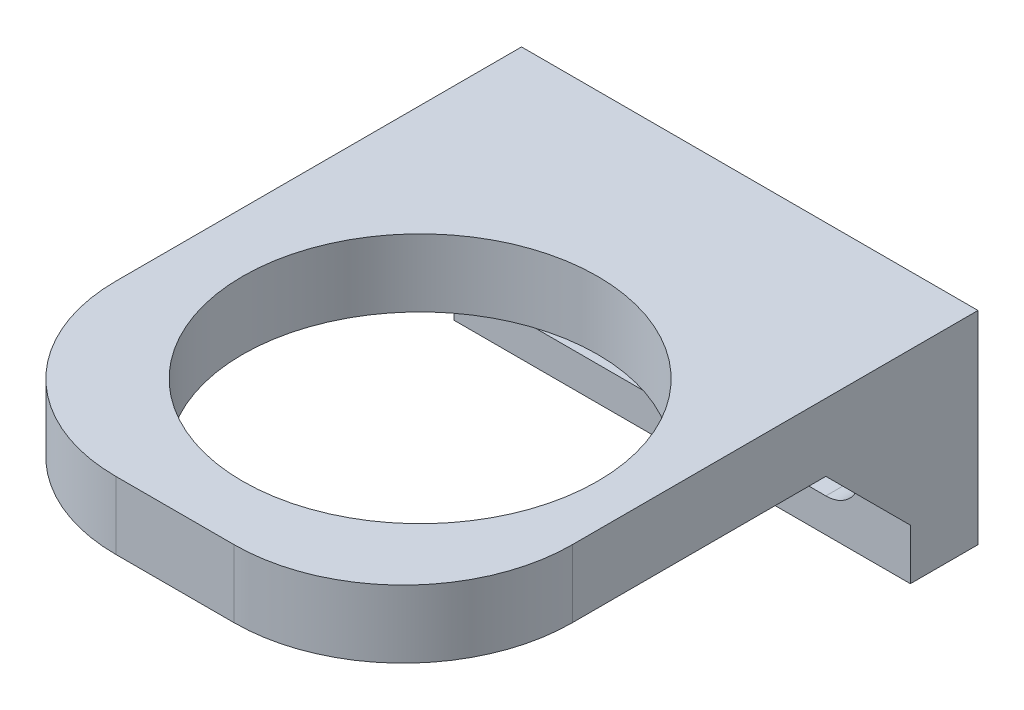
SolidWorks part; units mm, degrees
ref_plane "Plan de face" through (0, 0, 0) normal (0, 0, 1) x (1, 0, 0)
ref_plane "Plan de dessus" through (0, 0, 0) normal (0, 1, 0) x (1, 0, 0)
ref_plane "Plan de droite" through (0, 0, 0) normal (1, 0, 0) x (0, 0, -1)
sketch "Esquisse1" plane through (0, 0, 0) normal (0, 1, 0) x (1, 0, 0)
  line L1 (-14, 20) -> (13, 20)
  line L2 (-14, 20) -> (-14, -14)
  line L3 (-14, -14) -> (13, -14)
  line L4 (13, 20) -> (13, -14)
  line L6 (-14, 0) -> (13, 0) construction
  circle A0 centre (0, 0) radius 10.5
  dimension "D1" = 21
  dimension "D2" = 27
  dimension "D3" = 34
  dimension "D4" = 14
  dimension "D5" = 13
extrude "Boss.-Extru.1" add sketch "Esquisse1" along normal blind 4
sketch "Esquisse2" plane through (0, 0, 0) normal (0, -1, 0) x (1, 0, 0)
  line L0 (13, 14) -> (13, -20) construction
  line L1 (-14, -20) -> (13, -20)
  line L2 (-14, -20) -> (-14, -16)
  line L3 (-14, -16) -> (13, -16)
  line L4 (13, -20) -> (13, -16)
  dimension "D1" = 4
extrude "Boss.-Extru.2" add sketch "Esquisse2" along normal blind 8
sketch "Esquisse5" plane through (-14, 0, 0) normal (-1, 0, 0) x (0, 0, 1)
  line L0 (-16, 0) -> (-16, -5)
  line L1 (-16, -8) -> (-16, 0) construction
  line L2 (-16, -5) -> (-11, 0)
  line L3 (-16, 0) -> (14, 0) construction
  line L4 (-11, 0) -> (-16, 0)
  dimension "D1" = 45
  dimension "D2" = 5
extrude "Boss.-Extru.3" add sketch "Esquisse5" against normal blind 2
sketch "Esquisse6" plane through (13, 0, 0) normal (1, 0, 0) x (0, 0, -1)
  line L0 (16, 0) -> (11, 0)
  line L1 (-14, 0) -> (16, 0) construction
  line L2 (11, 0) -> (16, -5)
  line L3 (16, -8) -> (16, 0) construction
  line L4 (16, -5) -> (16, 0)
  dimension "D1" = 45
  dimension "D2" = 5
extrude "Boss.-Extru.4" add sketch "Esquisse6" against normal blind 2
fillet "Congé1" radius 10 2 edges at (-14, 2, 14) (13, 2, 14)
sketch "Esquisse7" plane through (0, 0, -16) normal (0, 0, 1) x (1, 0, 0)
  line L0 (-9, -4) -> (8, -4) construction
  line L1 (-9, -2) -> (8, -2)
  line L2 (-9, -6) -> (8, -6)
  line L3 (13, -8) -> (13, -5) construction
  line L4 (-14, -8) -> (-14, -5) construction
  line L5 (11, 0) -> (-12, 0) construction
  arc A0 (-9, -2) -> (-9, -6) centre (-9, -4) ccw
  arc A1 (8, -6) -> (8, -2) centre (8, -4) ccw
  point P2 (-0.5, -4)
  dimension "D1" = 4
  dimension "D2" = 5
  dimension "D3" = 5
  dimension "D4" = 4
extrude "Enlèv. mat.-Extru.1" cut sketch "Esquisse7" against normal through all
